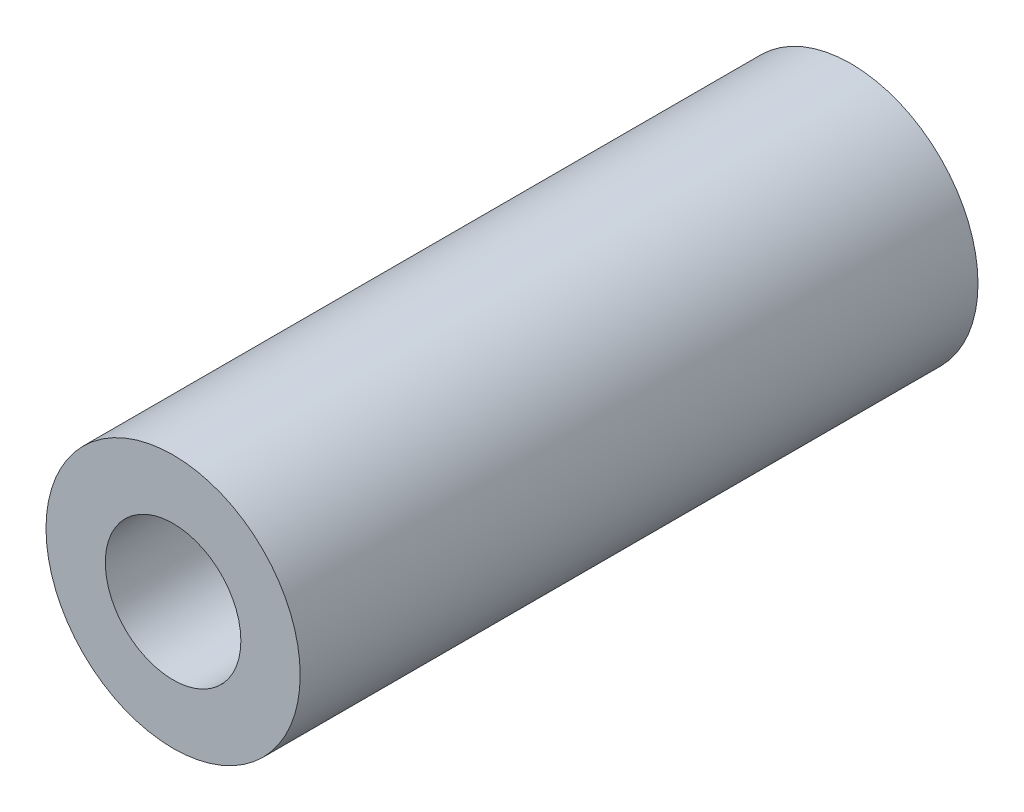
SolidWorks part; units mm, degrees
ref_plane "正面" through (0, 0, 0) normal (0, 0, 1) x (1, 0, 0)
ref_plane "平面" through (0, 0, 0) normal (0, 1, 0) x (1, 0, 0)
ref_plane "右側面" through (0, 0, 0) normal (1, 0, 0) x (0, 0, -1)
sketch "ｽｹｯﾁ1" plane through (0, 0, 0) normal (0, 0, 1) x (1, 0, 0)
  circle A0 centre (0, 0) radius 3
  circle A2 centre (0, 0) radius 1.6
  dimension "D1" = 3.2
  dimension "D2" = 6
extrude "ﾎﾞｽ - 押し出し1" add sketch "ｽｹｯﾁ1" along normal blind 16
